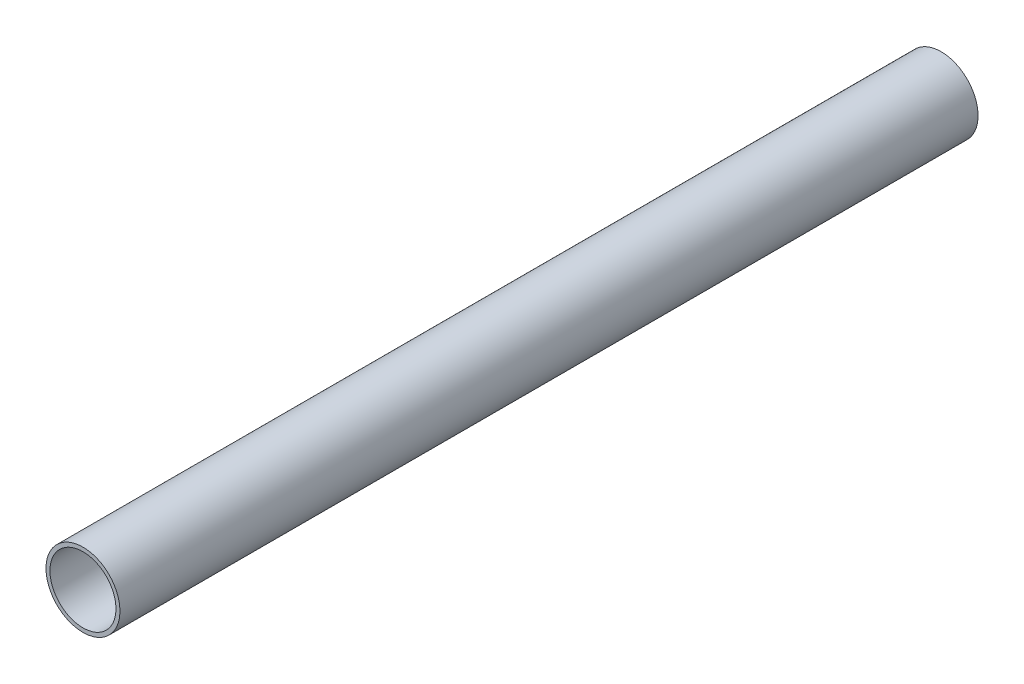
SolidWorks part; units mm, degrees
ref_plane "Front Plane" through (0, 0, 0) normal (0, 0, 1) x (1, 0, 0)
ref_plane "Top Plane" through (0, 0, 0) normal (0, 1, 0) x (1, 0, 0)
ref_plane "Right Plane" through (0, 0, 0) normal (1, 0, 0) x (0, 0, -1)
sketch "Sketch1" plane through (0, 0, -75) normal (0, 0, -1) x (-1, 0, 0)
  line L0 (0, 0) -> (0, 97.5) construction
  line L1 (-43.3013, 130) -> (43.3013, 130) construction
  circle A0 centre (0, 97.5) radius 12.5
  circle A1 centre (0, 97.5) radius 14
  dimension "D1" = 25
  dimension "D3" = 32.5
  dimension "D2" = 1.5
extrude "Boss-Extrude1" add sketch "Sketch1" along normal blind 325
